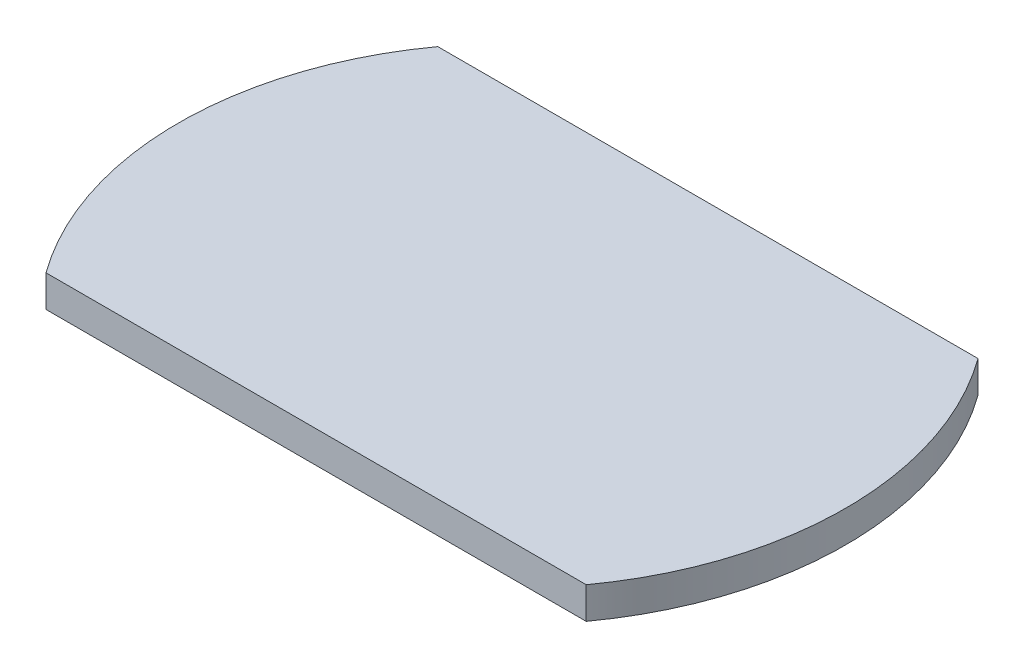
SolidWorks part; units mm, degrees
ref_plane "Plan de face" through (0, 0, 0) normal (0, 0, 1) x (1, 0, 0)
ref_plane "Plan de dessus" through (0, 0, 0) normal (0, 1, 0) x (1, 0, 0)
ref_plane "Plan de droite" through (0, 0, 0) normal (1, 0, 0) x (0, 0, -1)
sketch "Esquisse2" plane through (0, 0, 0) normal (0, 1, 0) x (1, 0, 0)
  line L0 (-85, -61.6441) -> (85, -61.6441)
  line L1 (85, 61.6441) -> (-85, 61.6441)
  arc A0 (85, -61.6441) -> (85, 61.6441) centre (0, 0) ccw
  arc A1 (-85, 61.6441) -> (-85, -61.6441) centre (0, 0) ccw
extrude "Boss.-Extru.1" add sketch "Esquisse2" along normal blind 10
